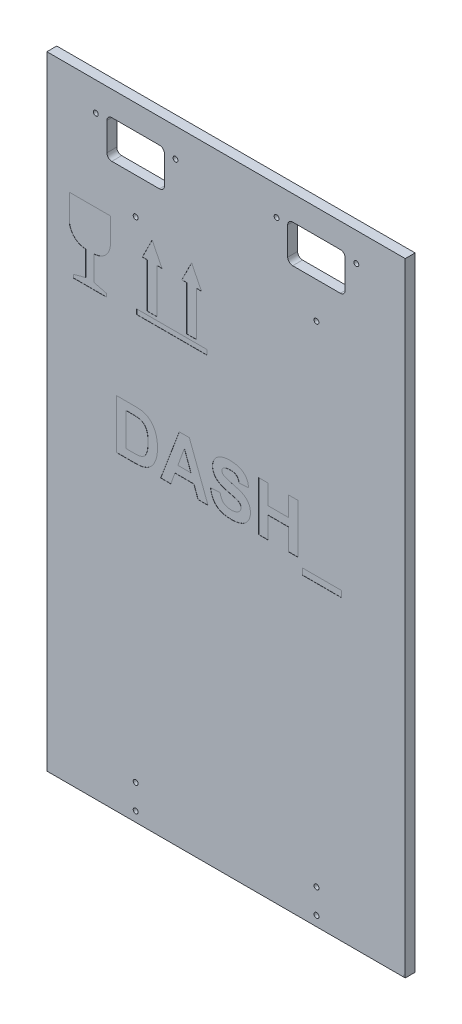
SolidWorks part; units mm, degrees
ref_plane "Спереди" through (0, 0, 0) normal (0, 0, 1) x (1, 0, 0)
ref_plane "Сверху" through (0, 0, 0) normal (0, 1, 0) x (1, 0, 0)
ref_plane "Справа" through (0, 0, 0) normal (1, 0, 0) x (0, 0, -1)
sketch "Эскиз1" plane through (0, 0, 0) normal (0, 0, 1) x (1, 0, 0)
  line L0 (-109, 326) -> (109, 326) construction
  line L1 (109, 332) -> (109, -60.5) construction
  line L2 (-109, -53) -> (109, -53) construction
  line L3 (-109, 332) -> (-109, -60.5) construction
  line L4 (-109, 326) -> (109, 326)
  line L5 (109, 326) -> (109, -53)
  line L6 (-109, -53) -> (109, -53)
  line L7 (-109, 326) -> (-109, -53)
  line L8 (0, 0) -> (0, 50000) construction
  line L9 (-55, -58.9588) -> (-55, -9.2224) construction
  line L10 (-70, -59) -> (-40, -59) construction
  line L11 (-55, 355.1773) -> (-55, 258.9299) construction
  line L12 (-40, 326) -> (-70, 326) construction
  line L13 (72.5, 288) -> (72.5, 311)
  line L14 (-37.5, 288) -> (-72.5, 288)
  line L15 (-37.5, 288) -> (-37.5, 311)
  line L16 (-37.5, 311) -> (-72.5, 311)
  line L17 (-72.5, 288) -> (-72.5, 311)
  line L18 (-37.5, 288) -> (-72.5, 311) construction
  line L19 (-37.5, 311) -> (-72.5, 288) construction
  line L20 (37.5, 311) -> (72.5, 311)
  line L21 (37.5, 288) -> (37.5, 311)
  line L22 (37.5, 288) -> (72.5, 288)
  circle A0 centre (-55, -47) radius 1.5
  circle A1 centre (-55, -32) radius 1.5
  circle A2 centre (55, -32) radius 1.5
  circle A3 centre (55, -47) radius 1.5
  circle A4 centre (-79.25, 308.5) radius 1.5
  circle A5 centre (-55, 266) radius 1.5
  circle A6 centre (-30.75, 308.5) radius 1.5
  circle A7 centre (30.75, 308.5) radius 1.5
  circle A8 centre (55, 266) radius 1.5
  circle A9 centre (79.25, 308.5) radius 1.5
  point P19 (-55, -59)
  point P28 (-55, 326)
  point P30 (-55, 299.5)
  point P46 (55, 299.5)
  dimension "D1" = 3
  dimension "D7" = 3
  dimension "D2" = 6
  dimension "D3" = 15
  dimension "D4" = 35
  dimension "D5" = 23
  dimension "D6" = 15
  dimension "D8" = 17.5
  dimension "D9" = 60
  dimension "D10" = 48.5
extrude "Бобышка-Вытянуть1" add sketch "Эскиз1" along normal blind 6
fillet "Скругление1" radius 3 8 edges at (37.5, 288, 3) (72.5, 288, 3) (72.5, 311, 3) (37.5, 311, 3) (-72.5, 311, 3) (-37.5, 311, 3) (-37.5, 288, 3) (-72.5, 288, 3)
sketch "Эскиз2" plane through (0, 0, 6) normal (0, 0, 1) x (1, 0, 0)
  line L0 (0, 0) -> (0, 50000) construction
  line L1 (-76.3917, 136.0063) -> (76.3917, 136.0063) construction
  line L2 (-82.8704, 289.2299) -> (-82.8704, 235.6213) construction
  line L3 (-92.8704, 214.8082) -> (-92.8704, 216.8082)
  line L4 (-92.8704, 216.8082) -> (-85.3704, 218.8082)
  line L5 (-85.3704, 218.8082) -> (-85.3704, 233.8082)
  line L6 (-95.3704, 243.8082) -> (-95.3704, 258.8082)
  line L7 (-95.3704, 258.8082) -> (-70.3704, 258.8082)
  line L8 (-70.3704, 243.8082) -> (-70.3704, 258.8082)
  line L9 (-80.3704, 218.8082) -> (-80.3704, 233.8082)
  line L10 (-72.8704, 216.8082) -> (-80.3704, 218.8082)
  line L11 (-72.8704, 214.8082) -> (-72.8704, 216.8082)
  line L12 (-92.8704, 214.8082) -> (-72.8704, 214.8082)
  line L13 (-32.9645, 216.3082) -> (-32.9645, 50216.3082) construction
  line L14 (-11.5225, 214.8082) -> (-54.4065, 214.8082)
  line L15 (-11.5225, 214.8082) -> (-11.5225, 217.8082)
  line L16 (-11.5225, 217.8082) -> (-54.4065, 217.8082)
  line L17 (-54.4065, 214.8082) -> (-54.4065, 217.8082)
  line L18 (-11.5225, 214.8082) -> (-54.4065, 217.8082) construction
  line L19 (-11.5225, 217.8082) -> (-54.4065, 214.8082) construction
  line L20 (-47.9645, 219.8082) -> (-47.9645, 246.8082)
  line L21 (-47.9645, 246.8082) -> (-50.9645, 246.8082)
  line L22 (-50.9645, 246.8082) -> (-44.9645, 258.8082)
  line L23 (-44.9645, 259.1492) -> (-44.9645, -49740.8508) construction
  line L24 (-47.9645, 219.8082) -> (-41.9645, 219.8082)
  line L25 (-38.9645, 246.8082) -> (-44.9645, 258.8082)
  line L26 (-41.9645, 246.8082) -> (-38.9645, 246.8082)
  line L27 (-41.9645, 219.8082) -> (-41.9645, 246.8082)
  line L28 (-23.9645, 219.8082) -> (-23.9645, 246.8082)
  line L29 (-23.9645, 246.8082) -> (-26.9645, 246.8082)
  line L30 (-26.9645, 246.8082) -> (-20.9645, 258.8082)
  line L31 (-17.9645, 219.8082) -> (-23.9645, 219.8082)
  line L32 (-14.9645, 246.8082) -> (-20.9645, 258.8082)
  line L33 (-17.9645, 246.8082) -> (-14.9645, 246.8082)
  line L34 (-17.9645, 219.8082) -> (-17.9645, 246.8082)
  circle A0 centre (108.386, -52.3431) radius 0.5
  arc A1 (-85.3704, 233.8082) -> (-95.3704, 243.8082) centre (-85.3704, 243.8082) cw
  arc A2 (-80.3704, 233.8082) -> (-70.3704, 243.8082) centre (-80.3704, 243.8082) ccw
  text T0 "DASH_" font "Arial" height 30
  point P9 (0, 136.0063)
  point P18 (-32.9645, 216.3082)
  dimension "D1" = 1
  dimension "D4" = 10
  dimension "D2" = 2
  dimension "D3" = 5
  dimension "D5" = 25
  dimension "D6" = 25
  dimension "D7" = 15
  dimension "D8" = 20
  dimension "D9" = 2
  dimension "D10" = 3
  dimension "D11" = 2
  dimension "D12" = 6
  dimension "D13" = 12
  dimension "D14" = 12
  dimension "D15" = 12
extrude "Вырез-Вытянуть1" cut sketch "Эскиз2" against normal blind 0.1
equation "\"D5@Эскиз1\"=15+8"
